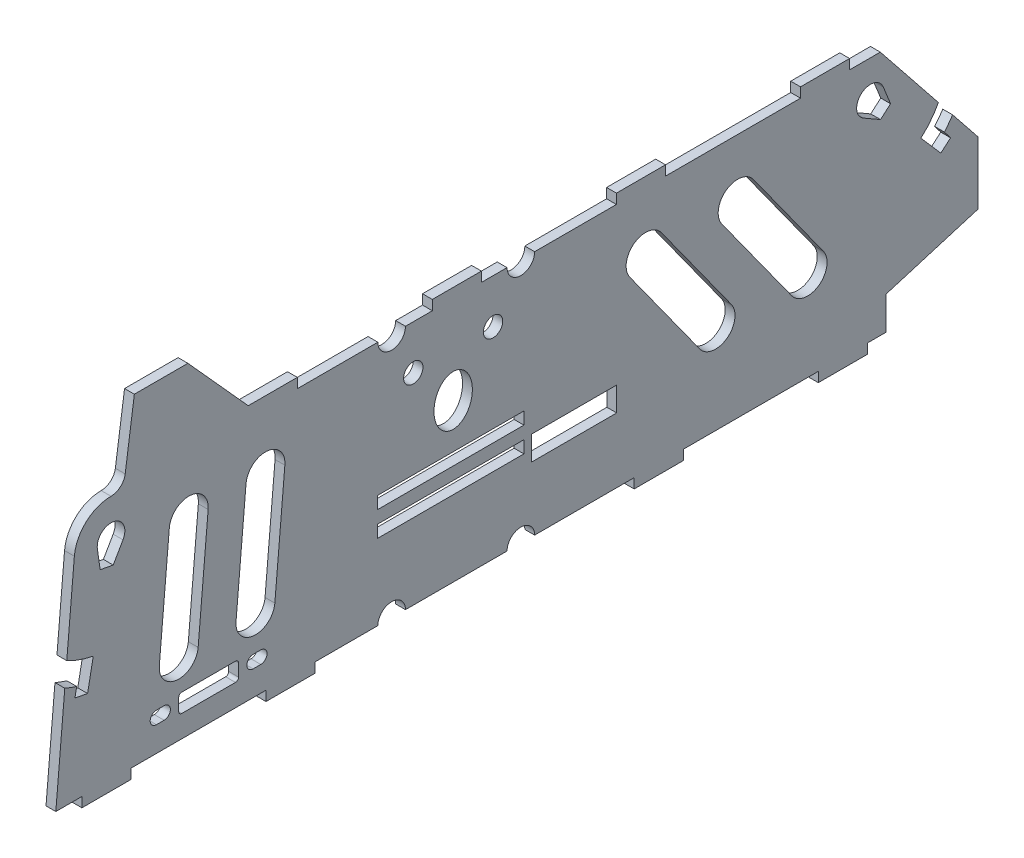
SolidWorks part; units mm, degrees
ref_plane "前视基准面" through (0, 0, 0) normal (0, 0, 1) x (1, 0, 0)
ref_plane "上视基准面" through (0, 0, 0) normal (0, 1, 0) x (1, 0, 0)
ref_plane "右视基准面" through (0, 0, 0) normal (1, 0, 0) x (0, 0, -1)
sketch "右侧结构" plane through (0, 0, 0) normal (1, 0, 0) x (0, 0, -1)
  line L0 (-44.2613, 14.3381) -> (-20.3822, 14.3381)
  line L1 (-96.6617, 0) -> (38.5883, 0)
  line L6 (-44.2613, 18.3959) -> (-20.3822, 18.3959)
  line L8 (-44.2613, 18.3959) -> (-44.2613, 16.3959)
  line L9 (-44.2613, 12.3381) -> (-20.3822, 12.3381)
  line L10 (-20.3822, 12.3381) -> (-20.3822, 14.3381)
  line L11 (-44.2613, 16.3959) -> (-20.3822, 16.3959)
  line L12 (-44.2613, 14.3381) -> (-44.2613, 12.3381)
  line L13 (-20.3822, 16.3959) -> (-20.3822, 18.3959)
  line L16 (-19.1356, 10.5554) -> (-5.2617, 10.5554)
  line L17 (-5.2617, 10.5554) -> (-5.2617, 14.5)
  line L18 (-5.2617, 14.5) -> (-19.1356, 14.5)
  line L19 (-19.1356, 14.5) -> (-19.1356, 10.5554)
  line L20 (-91.2196, 15.4465) -> (-91.4831, 14.0715)
  line L21 (36.0883, 34) -> (46.5716, 21.9389) construction
  line L22 (37.6933, 40) -> (-87.6642, 40)
  line L23 (-93.6414, 34.5229) -> (-96.6617, 0) construction
  line L25 (38.5883, 0) -> (38.5883, 38.8804) construction
  line L26 (38.5883, 38.8804) -> (37.6933, 40) construction
  line L36 (44.3048, 24.5469) -> (46.5716, 21.9389)
  line L39 (-87.6642, 34) -> (-91.2196, 15.4465) construction
  line L42 (-90.5609, 18.8839) -> (-91.2196, 15.4465)
  line L45 (-93.6414, 34.5229) -> (-94.8767, 20.4034)
  line L48 (-91.4831, 14.0715) -> (-93.5456, 14.4667)
  line L51 (-93.5456, 14.4667) -> (-93.2601, 15.9567)
  line L54 (46.5716, 21.9389) -> (47.5556, 20.8068)
  line L57 (38.5883, 38.8804) -> (53.614, 20.0824) construction
  line L60 (53.614, 20.0824) -> (53.614, 9.8778)
  line L66 (38.5883, 5.3637) -> (38.5883, 0)
  line L69 (47.5556, 20.8068) -> (49.1406, 22.1844)
  line L70 (49.1406, 22.1844) -> (48.1365, 23.5019)
  line L72 (38.1766, 34.8375) -> (39.3635, 31.8782)
  line L73 (39.3635, 31.8782) -> (38.5483, 31.1697)
  line L74 (38.5483, 31.1697) -> (37.7332, 30.4612)
  line L75 (37.7332, 30.4612) -> (34.968, 32.0487)
  line L77 (-88.37, 30.317) -> (-89.4307, 30.5203)
  line L78 (-89.4307, 30.5203) -> (-89.8907, 33.6754)
  line L88 (37.6933, 40) -> (47.164, 28.1517)
  line L91 (-88.37, 30.317) -> (-87.3093, 30.1138)
  line L92 (-87.3093, 30.1138) -> (-85.7155, 32.8753)
  line L97 (42.0237, 22.9708) -> (34.3307, 32.5952) construction
  line L107 (49.4706, 25.266) -> (53.614, 20.0824)
  line L108 (53.614, 9.8778) -> (38.5883, 5.3637)
  line L109 (42.0237, 22.9708) -> (44.209, 20.2369) construction
  line L110 (-95.2026, 16.6781) -> (-96.6617, 0)
  arc A0 (-87.6642, 40) -> (-93.6414, 34.5229) centre (-87.6642, 34) ccw
  circle A21 centre (36.0883, 34) radius 2.25
  arc A23 (47.164, 28.1517) -> (42.0237, 22.9708) centre (36.0883, 34) cw construction
  arc A24 (49.4706, 25.266) -> (44.209, 20.2369) centre (36.0883, 34) cw construction
  arc A25 (47.164, 28.1517) -> (44.3048, 24.5469) centre (36.0883, 34) cw
  arc A28 (49.4706, 25.266) -> (46.5716, 21.9389) centre (36.0883, 34) cw
  circle A31 centre (-87.6642, 34) radius 2.25
  arc A32 (-94.8767, 20.4034) -> (-90.5609, 18.8839) centre (-87.6642, 34) ccw
  arc A33 (-95.2026, 16.6781) -> (-91.2196, 15.4465) centre (-87.6642, 34) ccw
  arc A34 (-44.1822, 40) -> (-39.6822, 40) centre (-41.9322, 40) ccw
  arc A35 (-23.1322, 40) -> (-18.6322, 40) centre (-20.8822, 40) ccw
  arc A37 (-44.1822, 0) -> (-39.6822, 0) centre (-41.9322, 0) cw
  arc A38 (-23.1322, 0) -> (-18.6322, 0) centre (-20.8822, 0) cw
  dimension "D1" = 6
  dimension "D3" = 12.3381
  dimension "D11" = 135.25
  dimension "D13" = 4.5
  dimension "D14" = 6
  dimension "D19" = 3.5
  dimension "D20" = 2.25
  dimension "D30" = 3.75
  dimension "D2" = 40
  dimension "D4" = 1.7827
  dimension "D5" = 3.9446
  dimension "D6" = 23.8791
  dimension "D7" = 13.8739
  dimension "D8" = 1.2466
  dimension "D9" = 2.0578
  dimension "D10" = 2
  dimension "D12" = 85
  dimension "D15" = 43.85
  dimension "D16" = 3.5
  dimension "D17" = 5
  dimension "D18" = 2.5
  dimension "D21" = 21.55
  dimension "D22" = 0.5
  dimension "D23" = 1.4
  dimension "D24" = 2.1
  dimension "D25" = 12.3211
  dimension "D26" = 1.5
  dimension "D27" = 2.1
  dimension "D28" = 1.08
  dimension "D29" = 1.08
  dimension "D31" = 1.08
  dimension "D32" = 3.75
  dimension "D33" = 1.08
extrude "凸台-拉伸1" add sketch "右侧结构" along normal blind 1.6
sketch "草图2" plane through (0, 0, 0) normal (1, 0, 0) x (0, 0, -1)
  line L0 (35.5883, 0) -> (35.5883, -1.6)
  line L1 (-83.8627, 52.5) -> (-85.359, 42)
  line L2 (35.5883, -1.6) -> (27.5883, -1.6)
  line L3 (27.5883, -1.6) -> (27.5883, 0)
  line L4 (27.5883, 0) -> (35.5883, 0)
  line L5 (-83.8627, 52.5) -> (-75.1391, 52.5)
  line L6 (-2.4117, 0) -> (5.5883, 0)
  line L7 (5.5883, 0) -> (5.5883, -1.6)
  line L8 (5.5883, -1.6) -> (-2.4117, -1.6)
  line L9 (-2.4117, -1.6) -> (-2.4117, 0)
  line L10 (-32.4117, 0) -> (-24.4117, 0) construction
  line L11 (-24.4117, 0) -> (-24.4117, -1.6) construction
  line L12 (-24.4117, -1.6) -> (-32.4117, -1.6) construction
  line L13 (-32.4117, -1.6) -> (-32.4117, 0) construction
  line L14 (-62.4117, 0) -> (-54.4117, 0)
  line L15 (-54.4117, 0) -> (-54.4117, -1.6)
  line L16 (-54.4117, -1.6) -> (-62.4117, -1.6)
  line L17 (-62.4117, -1.6) -> (-62.4117, 0)
  line L18 (-92.4117, 0) -> (-84.4117, 0)
  line L19 (-84.4117, 0) -> (-84.4117, -1.6)
  line L20 (-84.4117, -1.6) -> (-92.4117, -1.6)
  line L21 (-92.4117, -1.6) -> (-92.4117, 0)
  line L22 (32.6933, 41.6) -> (32.6933, 40)
  line L23 (32.6933, 40) -> (24.6933, 40)
  line L24 (24.6933, 40) -> (24.6933, 41.6)
  line L25 (24.6933, 41.6) -> (32.6933, 41.6)
  line L26 (-75.1391, 52.5) -> (-65.3067, 41.6)
  line L27 (2.6933, 41.6) -> (2.6933, 40)
  line L28 (2.6933, 40) -> (-5.3067, 40)
  line L29 (-5.3067, 40) -> (-5.3067, 41.6)
  line L30 (-5.3067, 41.6) -> (2.6933, 41.6)
  line L31 (-27.3067, 41.6) -> (-27.3067, 40)
  line L32 (-27.3067, 40) -> (-35.3067, 40)
  line L33 (-35.3067, 40) -> (-35.3067, 41.6)
  line L34 (-35.3067, 41.6) -> (-27.3067, 41.6)
  line L35 (-57.3067, 41.6) -> (-57.3067, 40)
  line L36 (-57.3067, 40) -> (-65.3067, 40)
  line L37 (-65.3067, 40) -> (-65.3067, 41.6) construction
  line L38 (-65.3067, 41.6) -> (-57.3067, 41.6)
  line L39 (38.5883, 5.3637) -> (38.5883, 0) construction
  line L40 (-18.6322, 0) -> (38.5883, 0) construction
  line L41 (37.6933, 40) -> (-18.6322, 40) construction
  line L42 (-87.6642, 40) -> (-65.3067, 40)
  arc A0 (-87.6642, 40) -> (-85.359, 42) centre (-87.6642, 42.3285) ccw
  dimension "D1" = 3
  dimension "D2" = 1.6
  dimension "D3" = 8
  dimension "D5" = 1.6
  dimension "D6" = 8
  dimension "D7" = 5
  dimension "D9" = 12.5
  dimension "D4" = 5
  dimension "D8" = 4
extrude "上下板接口" add sketch "草图2" along normal up to surface (1.6 mm away) from surface at 0 up to face at (1.6, 32.5298, 87.9459) starting at face at (0, 32.5298, 87.9459)
sketch "天线接口-草图" plane through (1.6, 0, 0) normal (1, 0, 0) x (0, 0, -1)
  line L0 (38.5883, 0) -> (-117.1754, 0) construction
  line L1 (38.5883, -1000) -> (38.5883, 49000) construction
  line L2 (-38.4117, 32.7972) -> (-25.4117, 32.7972) construction
  line L3 (-31.9117, 25.6459) -> (-31.9117, 32.7972) construction
  line L6 (-44.2613, 16.3959) -> (-20.3822, 16.3959) construction
  circle A7 centre (-38.4117, 32.7972) radius 1.575
  circle A8 centre (-25.4117, 32.7972) radius 1.575
  ellipse E0 centre (-31.9117, 25.6459) end of major axis (-31.9117, 29.7253) minor radius 3.125
  dimension "D1" = 3.15
  dimension "D2" = 3.125
  dimension "D3" = 3.072
  dimension "D4" = 4.0794
  dimension "D5" = 13
  dimension "D6" = 70.5
  dimension "D7" = 9.25
extrude "天线接口" cut sketch "天线接口-草图" against normal through all
sketch "草图3" plane through (1.6, 0, 0) normal (1, 0, 0) x (0, 0, -1)
  line L0 (-75, 30.5) -> (-76.6317, 11.85) construction
  line L1 (-71.8371, 30.2233) -> (-73.4687, 11.5733)
  line L2 (-78.1629, 30.7767) -> (-79.7946, 12.1267)
  line L3 (-93.6414, 34.5229) -> (-94.8767, 20.4034) construction
  line L6 (14.45, 30.5) -> (25.8429, 14.6743) construction
  line L7 (17.0267, 32.355) -> (28.4196, 16.5293)
  line L8 (11.8733, 28.645) -> (23.2661, 12.8193)
  line L9 (-0.55, 30.5) -> (10.8429, 14.6743) construction
  line L12 (2.0267, 32.355) -> (13.4196, 16.5293)
  line L13 (-3.1267, 28.645) -> (8.2661, 12.8193)
  line L14 (14.45, 30.5) -> (-0.55, 30.5) construction
  line L15 (14.45, 30.5) -> (34.8658, 30.5) construction
  line L16 (-62.5, 30.5) -> (-64.1317, 11.85) construction
  line L17 (-59.3371, 30.2233) -> (-60.9687, 11.5733)
  line L18 (-65.6629, 30.7767) -> (-67.2946, 12.1267)
  line L19 (-75, 30.5) -> (-62.5, 30.5) construction
  arc A0 (-71.8371, 30.2233) -> (-78.1629, 30.7767) centre (-75, 30.5) ccw
  arc A1 (-79.7946, 12.1267) -> (-73.4687, 11.5733) centre (-76.6317, 11.85) ccw
  arc A4 (17.0267, 32.355) -> (11.8733, 28.645) centre (14.45, 30.5) ccw
  arc A5 (23.2661, 12.8193) -> (28.4196, 16.5293) centre (25.8429, 14.6743) ccw
  arc A8 (2.0267, 32.355) -> (-3.1267, 28.645) centre (-0.55, 30.5) ccw
  arc A9 (8.2661, 12.8193) -> (13.4196, 16.5293) centre (10.8429, 14.6743) ccw
  arc A10 (-59.3371, 30.2233) -> (-65.6629, 30.7767) centre (-62.5, 30.5) ccw
  arc A11 (-67.2946, 12.1267) -> (-60.9687, 11.5733) centre (-64.1317, 11.85) ccw
  point P2 (-75.8158, 21.175)
  point P11 (20.1464, 22.5872)
  point P20 (5.1464, 22.5872)
  point P30 (-63.3158, 21.175)
  dimension "D3" = 3.175
  dimension "D2" = 15
  dimension "D4" = 30.5
  dimension "D5" = 14.45
  dimension "D6" = 54.25
  dimension "D7" = 19.5
  dimension "D8" = 18.65
  dimension "D9" = 75
  dimension "D11" = 12.5
  dimension "D1" = 2
  dimension "D10" = 2
extrude "通风口-兼具天线捆扎功能" cut sketch "草图3" against normal through all
sketch "Sketch1" plane through (0, 0, 0) normal (1, 0, 0) x (0, 0, -1)
  line L0 (-76.1363, 6.5881) -> (-67.3863, 6.5881)
  line L1 (-76.6363, 6.0881) -> (-76.6363, 4.0881)
  line L2 (-71.7613, 6.5881) -> (-71.7613, -9.6698) construction
  line L3 (-66.8863, 6.0881) -> (-66.8863, 4.0881)
  line L4 (-76.6363, 5.0881) -> (-71.7613, 5.0881) construction
  line L5 (-76.1363, 3.5881) -> (-67.3863, 3.5881)
  line L6 (-44.2613, 14.3381) -> (-44.2613, 12.3381) construction
  line L7 (-44.2613, 12.3381) -> (-20.3822, 12.3381) construction
  line L8 (-79.0113, 5.0881) -> (-80.2613, 5.0881) construction
  line L9 (-79.0113, 4.0631) -> (-80.2613, 4.0631)
  line L10 (-79.0113, 6.1131) -> (-80.2613, 6.1131)
  line L11 (-64.5113, 5.0881) -> (-63.2613, 5.0881) construction
  line L12 (-64.5113, 4.0631) -> (-63.2613, 4.0631)
  line L13 (-64.5113, 6.1131) -> (-63.2613, 6.1131)
  circle A0 centre (-79.0113, 5.0881) radius 1.025 construction
  circle A1 centre (-64.5113, 5.0881) radius 1.025 construction
  arc A2 (-76.6363, 6.0881) -> (-76.1363, 6.5881) centre (-76.1363, 6.0881) cw
  arc A3 (-76.6363, 4.0881) -> (-76.1363, 3.5881) centre (-76.1363, 4.0881) ccw
  arc A4 (-66.8863, 6.0881) -> (-67.3863, 6.5881) centre (-67.3863, 6.0881) ccw
  arc A5 (-66.8863, 4.0881) -> (-67.3863, 3.5881) centre (-67.3863, 4.0881) cw
  arc A6 (-79.0113, 4.0631) -> (-79.0113, 6.1131) centre (-79.0113, 5.0881) ccw
  arc A7 (-80.2613, 6.1131) -> (-80.2613, 4.0631) centre (-80.2613, 5.0881) ccw
  arc A8 (-64.5113, 4.0631) -> (-64.5113, 6.1131) centre (-64.5113, 5.0881) cw
  arc A9 (-63.2613, 6.1131) -> (-63.2613, 4.0631) centre (-63.2613, 5.0881) cw
  point P17 (-79.6363, 5.0881)
  point P32 (-63.8863, 5.0881)
  dimension "D2" = 2.05
  dimension "D7" = 0.5
  dimension "D1" = 9.75
  dimension "D3" = 3
  dimension "D4" = 14.5
  dimension "D5" = 27.5
  dimension "D6" = 7.25
  dimension "D8" = 1.25
extrude "USB-C供电接口" cut sketch "Sketch1" along normal through all
